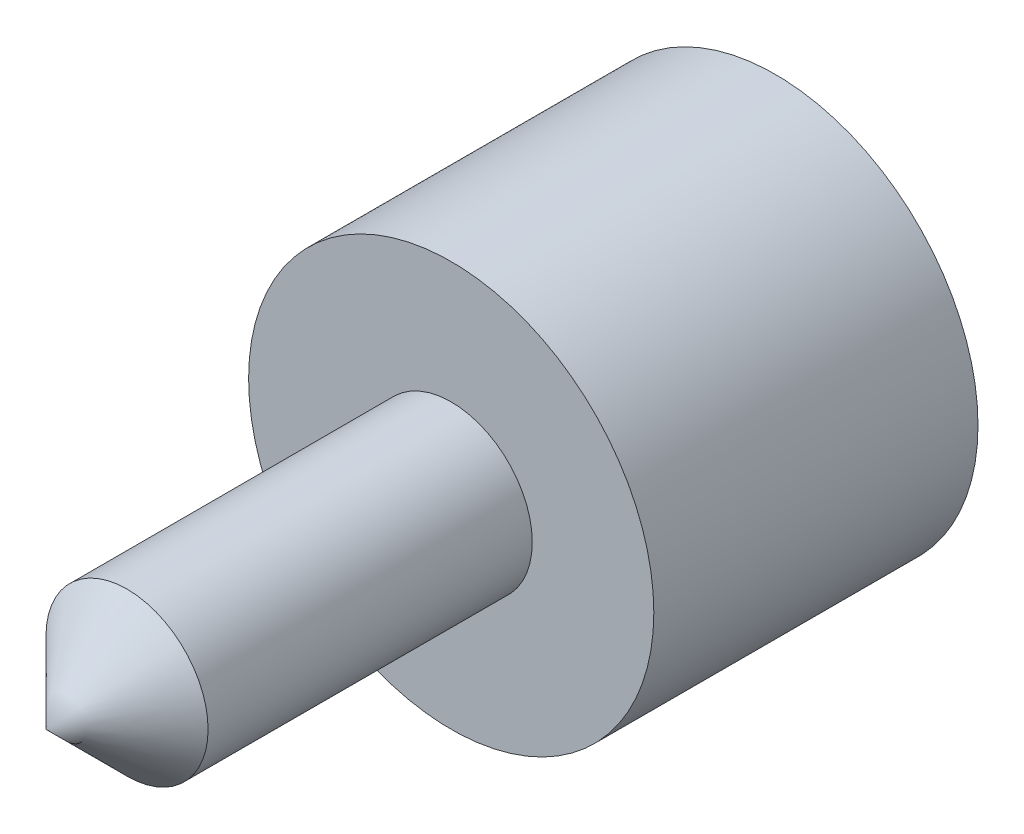
SolidWorks part; units mm, degrees
ref_plane "Alzado" through (0, 0, 0) normal (0, 0, 1) x (1, 0, 0)
ref_plane "Planta" through (0, 0, 0) normal (0, 1, 0) x (1, 0, 0)
ref_plane "Vista lateral" through (0, 0, 0) normal (1, 0, 0) x (0, 0, -1)
sketch "Croquis1" plane through (0, 0, 0) normal (0, 0, 1) x (1, 0, 0)
  circle A0 centre (0, 0) radius 5
  dimension "D1" = 10
extrude "Saliente-Extruir1" add sketch "Croquis1" along normal blind 8
sketch "Croquis2" plane through (0, 0, 0) normal (0, 0, -1) x (-1, 0, 0)
  circle A0 centre (0, 0) radius 1.25
  dimension "D1" = 2.5
extrude "Cortar-Extruir1" cut sketch "Croquis2" against normal blind 6
sketch "Croquis3" plane through (0, 0, 8) normal (0, 0, 1) x (1, 0, 0)
  circle A0 centre (0, 0) radius 2
  dimension "D1" = 4
extrude "Saliente-Extruir2" add sketch "Croquis3" along normal blind 10
chamfer "Chaflán1" distance 2 angle 45 1 edges at (2, 0, 18)
